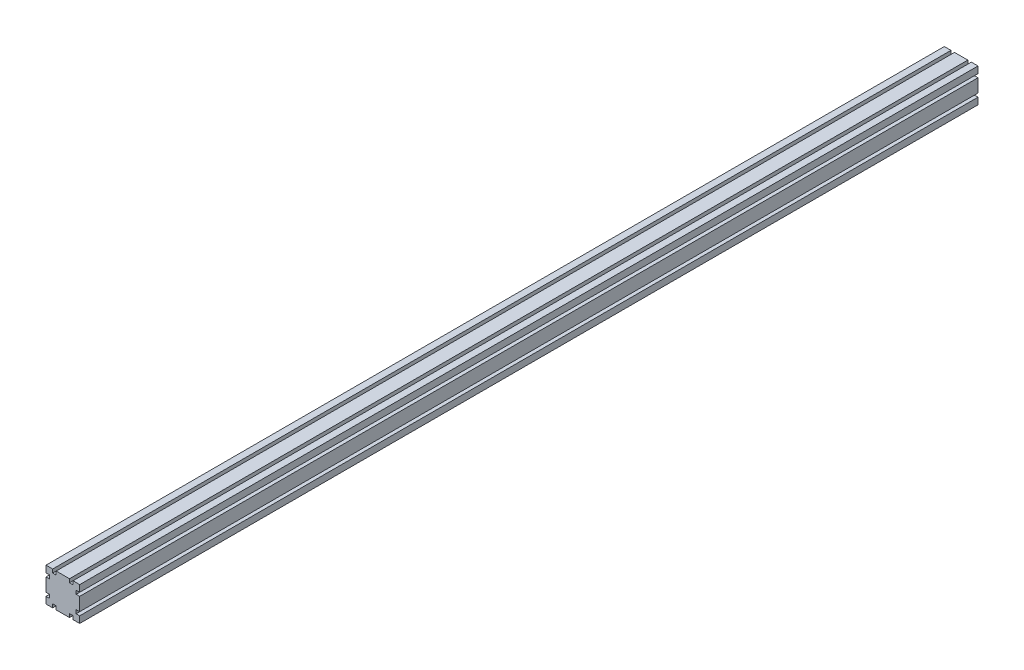
SolidWorks part; units mm, degrees
ref_plane "Front Plane" through (0, 0, 0) normal (0, 0, 1) x (1, 0, 0)
ref_plane "Top Plane" through (0, 0, 0) normal (0, 1, 0) x (1, 0, 0)
ref_plane "Right Plane" through (0, 0, 0) normal (1, 0, 0) x (0, 0, -1)
sketch "Sketch1" plane through (0, 0, 0) normal (0, 0, 1) x (1, 0, 0)
  line L0 (-38.1, -38.1) -> (-23.05, -38.1)
  line L1 (-23.05, -38.1) -> (-23.05, -30.1)
  line L2 (-23.05, -30.1) -> (-15.05, -30.1)
  line L3 (-15.05, -30.1) -> (-15.05, -38.1)
  line L4 (-15.05, -38.1) -> (15.05, -38.1)
  line L5 (15.05, -38.1) -> (15.05, -30.1)
  line L6 (15.05, -30.1) -> (23.05, -30.1)
  line L7 (23.05, -30.1) -> (23.05, -38.1)
  line L8 (23.05, -38.1) -> (38.1, -38.1)
  line L9 (38.1, -38.1) -> (38.1, -23.05)
  line L10 (38.1, -23.05) -> (30.1, -23.05)
  line L11 (30.1, -23.05) -> (30.1, -15.05)
  line L12 (30.1, -15.05) -> (38.1, -15.05)
  line L13 (38.1, -15.05) -> (38.1, 15.05)
  line L14 (38.1, 15.05) -> (30.1, 15.05)
  line L15 (30.1, 15.05) -> (30.1, 23.05)
  line L16 (30.1, 23.05) -> (38.1, 23.05)
  line L17 (38.1, 23.05) -> (38.1, 38.1)
  line L18 (38.1, 38.1) -> (23.05, 38.1)
  line L19 (23.05, 38.1) -> (23.05, 30.1)
  line L20 (23.05, 30.1) -> (15.05, 30.1)
  line L21 (15.05, 30.1) -> (15.05, 38.1)
  line L22 (15.05, 38.1) -> (-15.05, 38.1)
  line L23 (-15.05, 38.1) -> (-15.05, 30.1)
  line L24 (-15.05, 30.1) -> (-23.05, 30.1)
  line L25 (-23.05, 30.1) -> (-23.05, 38.1)
  line L26 (-23.05, 38.1) -> (-38.1, 38.1)
  line L27 (-38.1, 38.1) -> (-38.1, 23.05)
  line L28 (-38.1, 23.05) -> (-30.1, 23.05)
  line L29 (-30.1, 23.05) -> (-30.1, 15.05)
  line L30 (-30.1, 15.05) -> (-38.1, 15.05)
  line L31 (-38.1, 15.05) -> (-38.1, -15.05)
  line L32 (-38.1, -15.05) -> (-30.1, -15.05)
  line L33 (-30.1, -15.05) -> (-30.1, -23.05)
  line L34 (-30.1, -23.05) -> (-38.1, -23.05)
  line L35 (-38.1, -23.05) -> (-38.1, -38.1)
extrude "Profile" add sketch "Sketch1" along normal blind 2032
equation "\"length\" = 2032.0mm"
equation "\"D1@Profile\" = \"length\""
